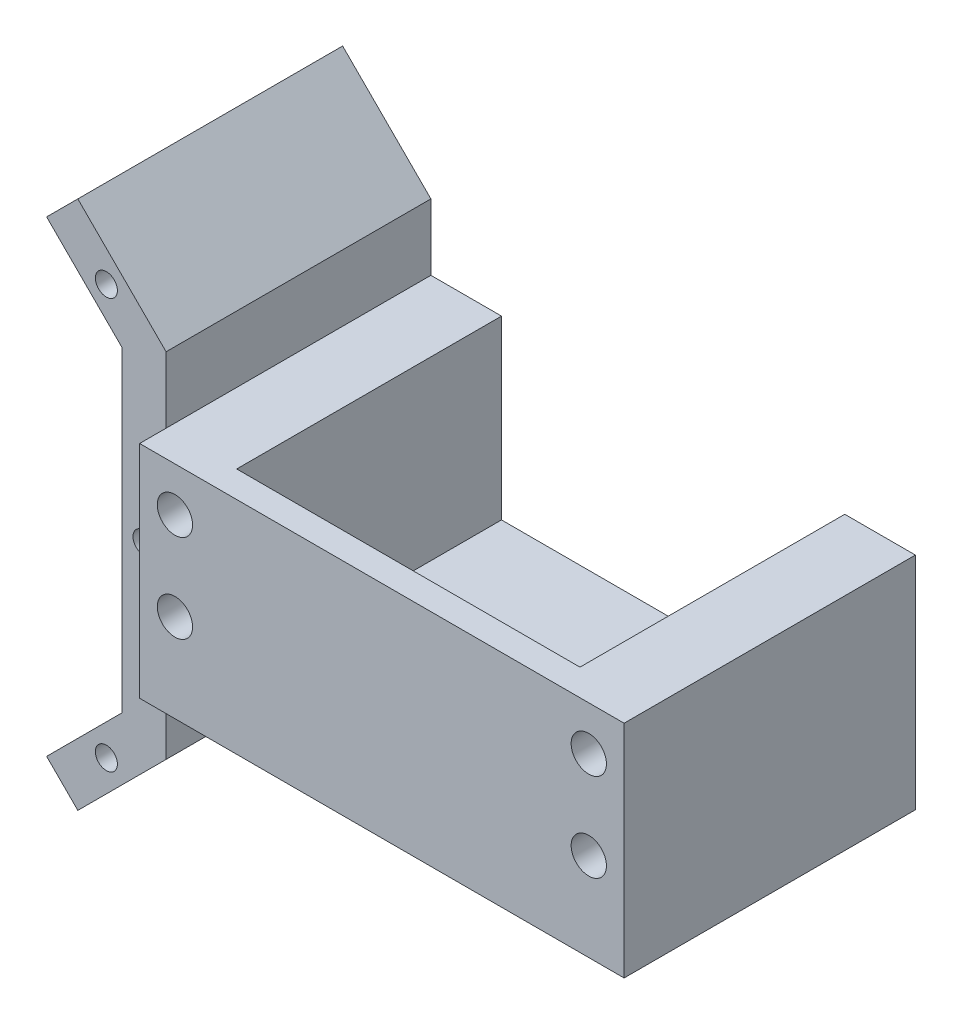
SolidWorks part; units mm, degrees
ref_plane "Front Plane" through (0, 0, 0) normal (0, 0, 1) x (1, 0, 0)
ref_plane "Top Plane" through (0, 0, 0) normal (0, 1, 0) x (1, 0, 0)
ref_plane "Right Plane" through (0, 0, 0) normal (1, 0, 0) x (0, 0, -1)
sketch "Model" plane through (0, 0, 0) normal (0, 0, 1) x (1, 0, 0)
  line L0 (29.6529, 16.2093) -> (29.6529, 56.2093)
  line L1 (24.6529, 18.2804) -> (24.6529, 54.1382)
  line L2 (29.6529, 16.2093) -> (19.6529, 6.2093)
  line L3 (24.6529, 18.2804) -> (16.1174, 9.7448)
  line L4 (29.6529, 56.2093) -> (19.6529, 66.2093)
  line L5 (24.6529, 54.1382) -> (16.1174, 62.6738)
  line L6 (19.6529, 6.2093) -> (16.1174, 9.7448)
  line L7 (19.6529, 66.2093) -> (16.1174, 62.6738)
  circle A0 centre (22.8852, 12.9771) radius 1.25
  circle A1 centre (27.1529, 36.2093) radius 1.25
  circle A2 centre (22.8852, 59.4415) radius 1.25
extrude "Boss-Extrude1" add sketch "Model" along normal blind 30
sketch "Sketch1" plane through (0, 0, 0) normal (0, 0, -1) x (-1, 0, 0)
  line L0 (-80.5429, 33.7093) -> (-80.5429, 43.7093) construction
  line L1 (-29.6529, 16.2093) -> (-29.6529, 56.2093) construction
  line L2 (-37.6529, 28.7093) -> (-76.5429, 28.7093)
  line L7 (-37.6529, 48.7093) -> (-29.6529, 48.7093)
  line L8 (-37.6529, 48.7093) -> (-37.6529, 28.7093)
  line L10 (-29.6529, 48.7093) -> (-29.6529, 28.7093)
  line L11 (-29.6529, 28.7093) -> (-29.6529, 23.7093)
  line L12 (-29.6529, 23.7093) -> (-76.5429, 23.7093)
  line L14 (-76.5429, 23.7093) -> (-84.5429, 23.7093)
  line L15 (-76.5429, 28.7093) -> (-76.5429, 48.7093)
  line L16 (-76.5429, 48.7093) -> (-84.5429, 48.7093)
  line L17 (-84.5429, 23.7093) -> (-84.5429, 48.7093)
  line L18 (-76.5429, 38.7093) -> (-84.5429, 38.7093) construction
  line L19 (-57.0979, 28.7093) -> (-57.0979, 50.6337) construction
  circle A0 centre (-80.5429, 33.7093) radius 2
  circle A1 centre (-80.5429, 43.7093) radius 2
  circle A2 centre (-33.6529, 33.7093) radius 2
  circle A3 centre (-33.6529, 43.7093) radius 2
  point P4 (-37.6529, 36.2093)
  point P18 (-80.5429, 38.7093)
  dimension "D1" = 7.5
  dimension "D2" = 5
extrude "Boss-Extrude3" add sketch "Sketch1" against normal blind 33
sketch "Sketch3" plane through (0, 0, 33) normal (0, 0, 1) x (1, 0, 0)
  line L1 (37.6529, 48.7093) -> (76.5429, 48.7093)
  line L2 (37.6529, 48.7093) -> (37.6529, 28.7093)
  line L3 (37.6529, 28.7093) -> (76.5429, 28.7093)
  line L4 (76.5429, 48.7093) -> (76.5429, 28.7093)
extrude "Boss-Extrude6" add sketch "Sketch3" against normal blind 3
